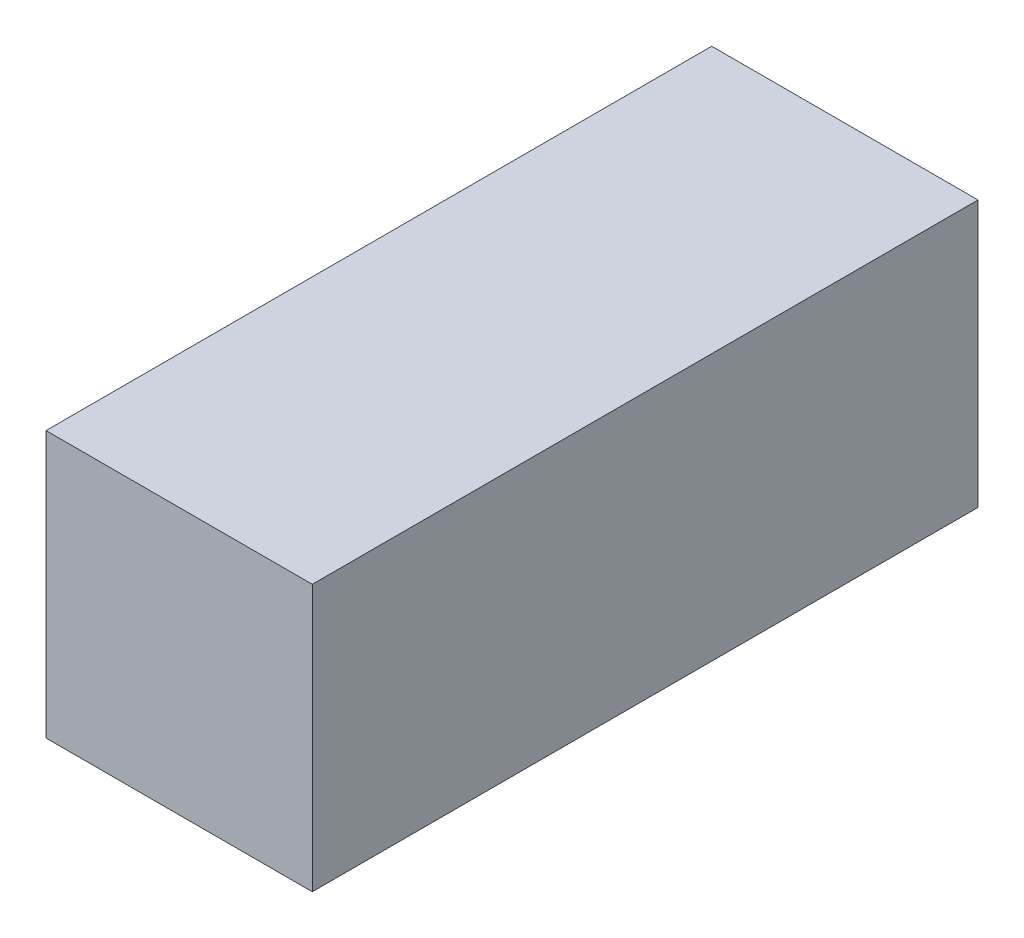
SolidWorks part; units mm, degrees
ref_plane "前视基准面" through (0, 0, 0) normal (0, 0, 1) x (1, 0, 0)
ref_plane "上视基准面" through (0, 0, 0) normal (0, 1, 0) x (1, 0, 0)
ref_plane "右视基准面" through (0, 0, 0) normal (1, 0, 0) x (0, 0, -1)
sketch "草图1" plane through (0, 0, 0) normal (0, 0, 1) x (1, 0, 0)
  line L0 (-21.8405, 23.4666) -> (-21.8405, -16.5334)
  line L1 (-21.8405, 23.4666) -> (18.1595, 23.4666)
  line L2 (18.1595, -16.5334) -> (-21.8405, -16.5334)
  line L3 (18.1595, 23.4666) -> (18.1595, -16.5334)
  dimension "D1" = 40
  dimension "D2" = 40
extrude "凸台-拉伸1" add sketch "草图1" along normal blind 100
